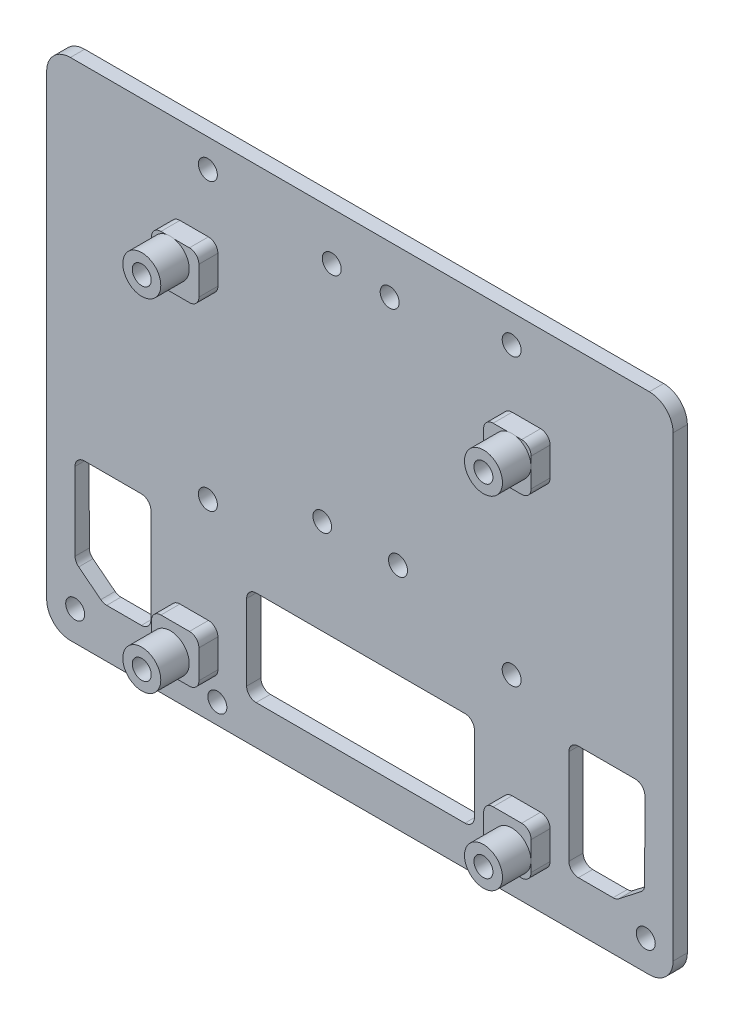
SolidWorks part; units mm, degrees
ref_plane "Front Plane" through (0, 0, 0) normal (0, 0, 1) x (1, 0, 0)
ref_plane "Top Plane" through (0, 0, 0) normal (0, 1, 0) x (1, 0, 0)
ref_plane "Right Plane" through (0, 0, 0) normal (1, 0, 0) x (0, 0, -1)
other "Graphic1"
ref_plane "Plane1" through (0, 0, 10) normal (0, 0, 1) x (1, 0, 0)
sketch "Sketch1" plane through (0, 0, 10) normal (0, 0, 1) x (1, 0, 0)
  line L1 (144.9639, 320.0391) -> (210.9639, 320.0391)
  line L2 (144.9639, 320.0391) -> (144.9639, 266.8391)
  line L3 (144.9639, 266.8391) -> (210.9639, 266.8391)
  line L4 (210.9639, 320.0391) -> (210.9639, 266.8391)
  circle A0 centre (161.9475, 317.0605) radius 1
  circle A1 centre (193.9565, 317.0605) radius 1
  circle A2 centre (174.9978, 314.9828) radius 1
  circle A3 centre (181.1009, 314.9828) radius 1
  circle A4 centre (173.9978, 290.9653) radius 0.9833
  circle A5 centre (181.9833, 290.9653) radius 1
  circle A6 centre (161.9475, 286.9627) radius 1
  circle A7 centre (193.9565, 286.9627) radius 1
  circle A8 centre (162.9475, 268.9705) radius 1
  circle A9 centre (192.9565, 268.9705) radius 1.0113
  circle A10 centre (208.0846, 269.9818) radius 1
  circle A11 centre (147.9666, 269.9705) radius 1
  dimension "D1" = 66
  dimension "D2" = 53.2
extrude "Boss-Extrude1" add sketch "Sketch1" along normal blind 1.5
sketch "Sketch2" plane through (0, 0, 11.5) normal (0, 0, 1) x (1, 0, 0)
  line L0 (193.0042, 310.9393) -> (193.0042, 305.9393)
  line L1 (158.0042, 310.9393) -> (163.0042, 310.9393)
  line L2 (158.0042, 310.9393) -> (158.0042, 305.9393)
  line L3 (158.0042, 305.9393) -> (163.0042, 305.9393)
  line L4 (163.0042, 310.9393) -> (163.0042, 305.9393)
  line L5 (193.0042, 310.9393) -> (198.0042, 310.9393)
  line L6 (198.0042, 310.9393) -> (198.0042, 305.9393)
  line L7 (193.0042, 305.9393) -> (198.0042, 305.9393)
  line L8 (193.0042, 275.9393) -> (193.0042, 270.9393)
  line L9 (193.0042, 275.9393) -> (198.0042, 275.9393)
  line L10 (198.0042, 275.9393) -> (198.0042, 270.9393)
  line L11 (193.0042, 270.9393) -> (198.0042, 270.9393)
  line L12 (158.0042, 275.9393) -> (158.0042, 270.9393)
  line L13 (158.0042, 275.9393) -> (163.0042, 275.9393)
  line L14 (163.0042, 275.9393) -> (163.0042, 270.9393)
  line L15 (158.0042, 270.9393) -> (163.0042, 270.9393)
  dimension "D1" = 5
  dimension "D2" = 5
  dimension "D3" = 2
  dimension "D4" = 2
extrude "Boss-Extrude2" add sketch "Sketch2" along normal blind 2
fillet "Fillet1" radius 1 16 edges at (158.0042, 275.9393, 12.5) (163.0042, 275.9393, 12.5) (163.0042, 270.9393, 12.5) (158.0042, 270.9393, 12.5) (198.0042, 275.9393, 12.5) (193.0042, 275.9393, 12.5) (198.0042, 270.9393, 12.5) (193.0042, 270.9393, 12.5) (193.0042, 305.9393, 12.5) (193.0042, 310.9393, 12.5) (198.0042, 305.9393, 12.5) (198.0042, 310.9393, 12.5) (158.0042, 310.9393, 12.5) (163.0042, 310.9393, 12.5) (163.0042, 305.9393, 12.5) (158.0042, 305.9393, 12.5)
fillet "Fillet2" radius 2.5 4 edges at (144.9639, 320.0391, 10.75) (210.9639, 320.0391, 10.75) (210.9639, 266.8391, 10.75) (144.9639, 266.8391, 10.75)
sketch "Sketch3" plane through (0, 0, 13.5) normal (0, 0, 1) x (1, 0, 0)
  circle A0 centre (159.9868, 308.9933) radius 2
  circle A1 centre (195.9868, 308.9933) radius 2
  circle A2 centre (195.9868, 272.9933) radius 2
  circle A3 centre (159.9868, 272.9933) radius 2
  point P2 (169.9868, 308.9933)
  dimension "D1" = 2
  dimension "D2" = 2
extrude "Boss-Extrude3" add sketch "Sketch3" along normal blind 3
sketch "Sketch4" plane through (0, 0, 16.5) normal (0, 0, 1) x (1, 0, 0)
  circle A0 centre (159.9799, 308.9671) radius 1
  circle A1 centre (195.9799, 308.9671) radius 1
  circle A2 centre (195.9799, 272.9671) radius 1
  circle A3 centre (159.9799, 272.9671) radius 1
  point P6 (169.9799, 308.9671)
  point P7 (169.9799, 308.9671)
  point P8 (159.9799, 298.9671)
  dimension "D1" = 2
  dimension "D2" = 2
extrude "Cut-Extrude1" cut sketch "Sketch4" against normal through all
sketch "Sketch5" plane through (0, 0, 11.5) normal (0, 0, 1) x (1, 0, 0)
  line L0 (199.987, 283.9594) -> (207.987, 283.9594)
  line L1 (207.987, 283.9594) -> (207.9709, 274.2894)
  line L2 (207.9709, 274.2894) -> (204.987, 271.9594)
  line L3 (204.987, 271.9594) -> (199.987, 271.9594)
  line L4 (199.987, 271.9594) -> (199.987, 283.9594)
  line L5 (177.9639, 266.8391) -> (177.9639, 261.7896) construction
  line L6 (147.4639, 266.8391) -> (208.4639, 266.8391) construction
  line L7 (150.9409, 271.9594) -> (155.9409, 271.9594)
  line L8 (147.957, 274.2894) -> (150.9409, 271.9594)
  line L9 (147.9409, 283.9594) -> (147.957, 274.2894)
  line L10 (155.9409, 283.9594) -> (147.9409, 283.9594)
  line L11 (155.9409, 271.9594) -> (155.9409, 283.9594)
  line L13 (166.0306, 280.9606) -> (190.0306, 280.9606)
  line L14 (166.0306, 280.9606) -> (166.0306, 270.9606)
  line L15 (166.0306, 270.9606) -> (190.0306, 270.9606)
  line L16 (190.0306, 280.9606) -> (190.0306, 270.9606)
  dimension "D1" = 8
  dimension "D2" = 9.67
  dimension "D3" = 5
  dimension "D4" = 12
  dimension "D5" = 24
  dimension "D6" = 10
extrude "Cut-Extrude2" cut sketch "Sketch5" against normal blind 3
fillet "Fillet3" radius 1 14 edges at (190.0306, 270.9606, 10.75) (166.0306, 270.9606, 10.75) (166.0306, 280.9606, 10.75) (190.0306, 280.9606, 10.75) (147.957, 274.2894, 10.75) (147.9409, 283.9594, 10.75) (155.9409, 283.9594, 10.75) (155.9409, 271.9594, 10.75) (150.9409, 271.9594, 10.75) (204.987, 271.9594, 10.75) (207.9709, 274.2894, 10.75) (207.987, 283.9594, 10.75) (199.987, 271.9594, 10.75) (199.987, 283.9594, 10.75)
